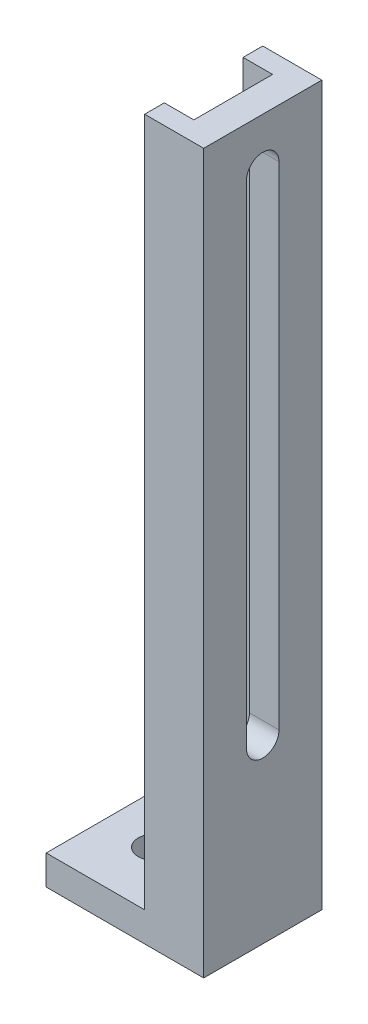
SolidWorks part; units mm, degrees
ref_plane "前视基准面" through (0, 0, 0) normal (0, 0, 1) x (1, 0, 0)
ref_plane "上视基准面" through (0, 0, 0) normal (0, 1, 0) x (1, 0, 0)
ref_plane "右视基准面" through (0, 0, 0) normal (1, 0, 0) x (0, 0, -1)
sketch "草图1" plane through (0, 0, 0) normal (0, 1, 0) x (1, 0, 0)
  line L1 (3, -6) -> (-3, -6)
  line L2 (3, -6) -> (3, 6)
  line L3 (3, 6) -> (-3, 6)
  line L4 (-3, -6) -> (-3, 6)
  line L5 (3, -6) -> (-3, 6) construction
  line L6 (3, 6) -> (-3, -6) construction
  point P0 (0, 0)
  dimension "D1" = 6
  dimension "D2" = 12
extrude "凸台-拉伸1" add sketch "草图1" along normal blind 70
sketch "草图2" plane through (0, 0, 0) normal (0, 1, 0) x (1, 0, 0)
  line L1 (3, 6) -> (-13, 6)
  line L2 (3, 6) -> (3, -6)
  line L3 (3, -6) -> (-13, -6)
  line L4 (-13, 6) -> (-13, -6)
  dimension "D1" = 12
  dimension "D2" = 16
extrude "凸台-拉伸2" add sketch "草图2" against normal blind 3
sketch "草图3" plane through (0, 0, 0) normal (0, 1, 0) x (1, 0, 0)
  line L0 (-3, 6) -> (-13, 6) construction
  line L1 (-13, 6) -> (-13, -6) construction
  circle A0 centre (-8, 0) radius 1.65
  dimension "D1" = 3.3
  dimension "D3" = 5
  dimension "D2" = 6
extrude "切除-拉伸1" cut sketch "草图3" against normal up to surface (3 mm away) up to face at (-5, -3, 0)
sketch "草图4" plane through (-3, 0, 0) normal (1, 0, 0) x (0, 0, -1)
  line L0 (-6, 70) -> (6, 70) construction
  line L1 (4, 70) -> (-4, 70)
  line L2 (4, 70) -> (4, 10)
  line L3 (4, 10) -> (-4, 10)
  line L4 (-4, 70) -> (-4, 10)
  line L5 (6, 70) -> (6, -3) construction
  line L6 (-6, 70) -> (-6, -3) construction
  dimension "D1" = 2
  dimension "D2" = 2
  dimension "D3" = 60
extrude "切除-拉伸2" cut sketch "草图4" along normal blind 3
sketch "草图5" plane through (0, 0, 0) normal (-1, 0, 0) x (0, 0, 1)
  line L0 (0, 65) -> (0, 15) construction
  line L1 (1.65, 65) -> (1.65, 15)
  line L2 (-1.65, 65) -> (-1.65, 15)
  line L3 (4, 10) -> (-4, 10) construction
  arc A0 (1.65, 65) -> (-1.65, 65) centre (0, 65) ccw
  arc A1 (-1.65, 15) -> (1.65, 15) centre (0, 15) ccw
  point P3 (0, 40)
  dimension "D1" = 1.65
  dimension "D3" = 5
  dimension "D2" = 50
extrude "切除-拉伸3" cut sketch "草图5" against normal up to surface (3 mm away) up to face at (3, 33.5, 0)
